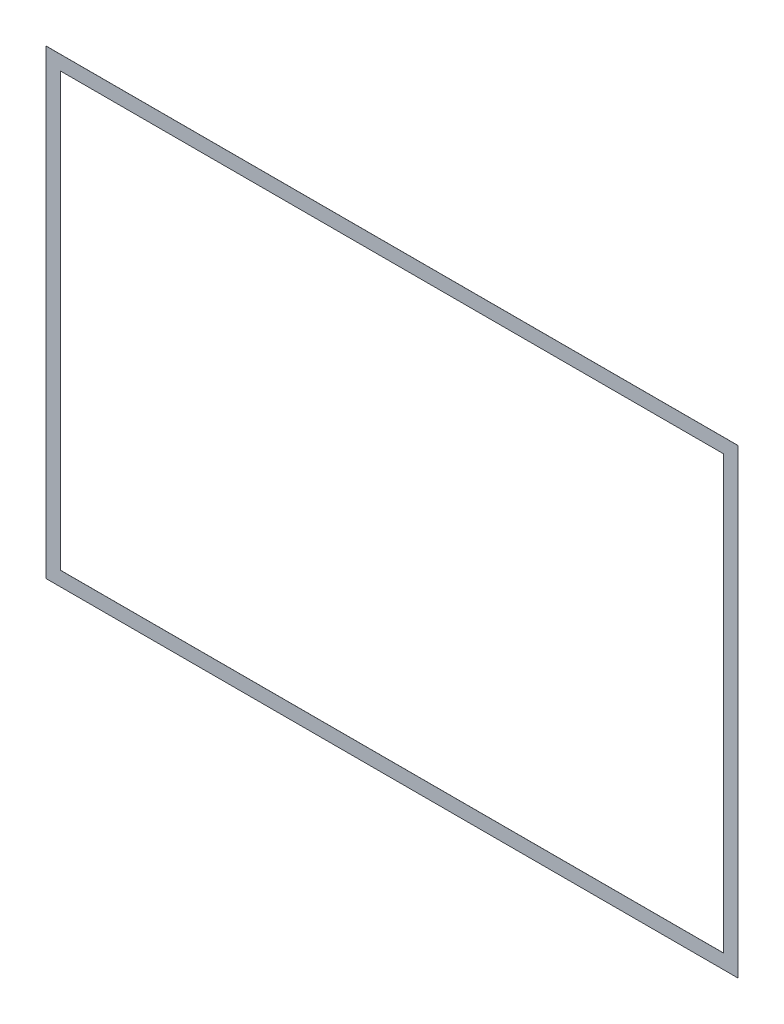
SolidWorks part; units mm, degrees
ref_plane "Front Plane" through (0, 0, 0) normal (0, 0, 1) x (1, 0, 0)
ref_plane "Top Plane" through (0, 0, 0) normal (0, 1, 0) x (1, 0, 0)
ref_plane "Right Plane" through (0, 0, 0) normal (1, 0, 0) x (0, 0, -1)
sketch "Sketch4" plane through (0, 0, 0) normal (0, 0, 1) x (1, 0, 0)
  line L1 (-287.5, 187.5) -> (287.5, 187.5)
  line L2 (-287.5, 187.5) -> (-287.5, -187.5)
  line L3 (-287.5, -187.5) -> (287.5, -187.5)
  line L4 (287.5, 187.5) -> (287.5, -187.5)
  line L5 (-287.5, 187.5) -> (287.5, -187.5) construction
  line L6 (-287.5, -187.5) -> (287.5, 187.5) construction
  line L7 (-300, 200) -> (300, 200)
  line L8 (-300, 200) -> (-300, -200)
  line L9 (-300, -200) -> (300, -200)
  line L10 (300, 200) -> (300, -200)
  line L11 (-300, 200) -> (300, -200) construction
  line L12 (-300, -200) -> (300, 200) construction
  point P0 (0, 0)
  point P6 (0, 0)
  dimension "D1" = 12.5
  dimension "D2" = 12.5
  dimension "D3" = 575
  dimension "D4" = 400
  dimension "D5" = 375
extrude "Boss-Extrude4" add sketch "Sketch4" along normal mid plane 0.052
